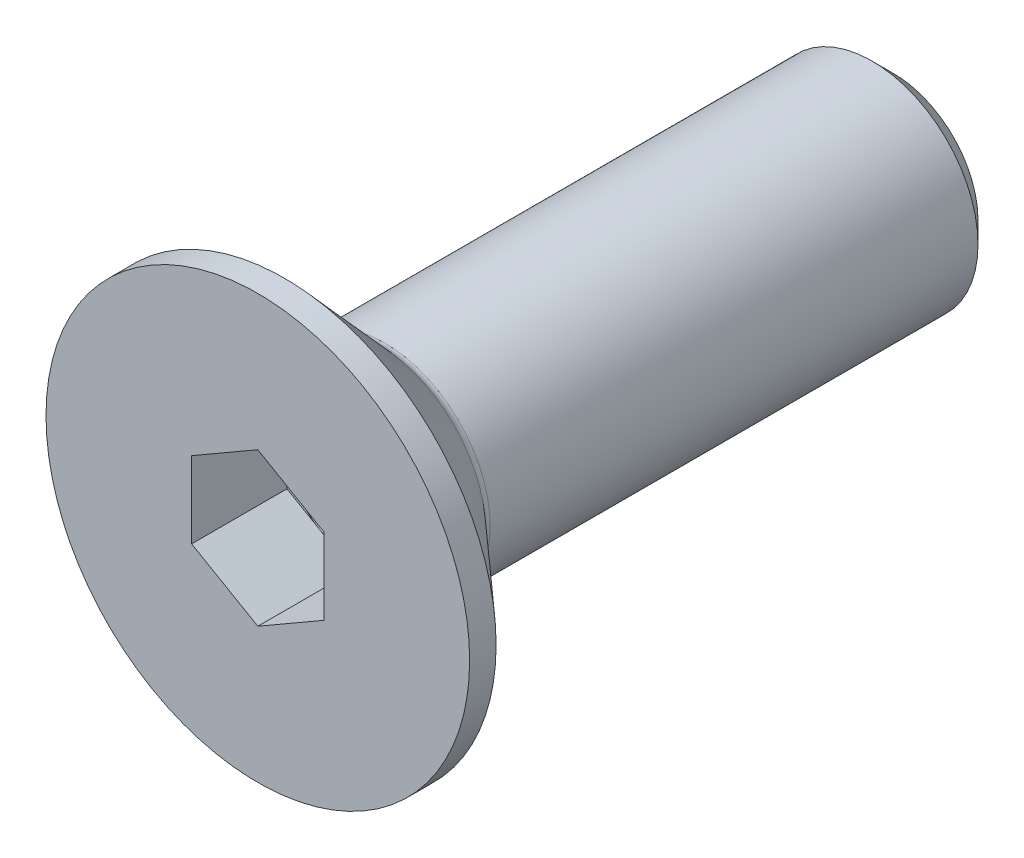
SolidWorks part; units mm, degrees
ref_plane "Plano frontal" through (0, 0, 0) normal (0, 0, 1) x (1, 0, 0)
ref_plane "Plano superior" through (0, 0, 0) normal (0, 1, 0) x (1, 0, 0)
ref_plane "Plano direito" through (0, 0, 0) normal (1, 0, 0) x (0, 0, -1)
sketch "Esboço4" plane through (0, 0, 0) normal (1, 0, 0) x (0, 0, -1)
  line L0 (0, 4) -> (0, 0)
  line L1 (0, 0) -> (12, 0)
  line L4 (12, 0) -> (12, 2)
  line L5 (12, 2) -> (2.3, 2)
  line L6 (2.3, 2) -> (0.5, 4)
  line L7 (0.5, 4) -> (0, 4)
  line L8 (0, 0) -> (12, 0) construction
  dimension "D1" = 8
  dimension "D2" = 0.5
  dimension "D3" = 4
  dimension "D4" = 2.3
  dimension "D5" = 12
revolve "Revolução1" add sketch "Esboço4" angle 360 about L8
chamfer "Chanfro1" distance 0.4 angle 45 1 edges at (2, 0, -12)
sketch "Esboço5" plane through (0, 0, 0) normal (0, 0, 1) x (1, 0, 0)
  line L1 (-1.25, -0.7217) -> (0, -1.4434)
  line L2 (0, -1.4434) -> (1.25, -0.7217)
  line L3 (1.25, -0.7217) -> (1.25, 0.7217)
  line L4 (1.25, 0.7217) -> (0, 1.4434)
  line L5 (0, 1.4434) -> (-1.25, 0.7217)
  line L6 (-1.25, 0.7217) -> (-1.25, -0.7217)
  circle A0 centre (0, 0) radius 1.25 construction
  dimension "D1" = 2.5
extrude "Corte-extrusão1" cut sketch "Esboço5" against normal blind 1.8
sketch "Esboço6" plane through (0, 0, -1.8) normal (0, 0, 1) x (1, 0, 0)
  line L0 (-1.25, -0.7217) -> (0, -1.4434) construction
  circle A0 centre (0, 0) radius 1.25
extrude "Corte-extrusão2" cut sketch "Esboço6" against normal blind 0.5 draft 69
fillet "Filete1" radius 0.2 1 edges at (2, 0, -2.3)
